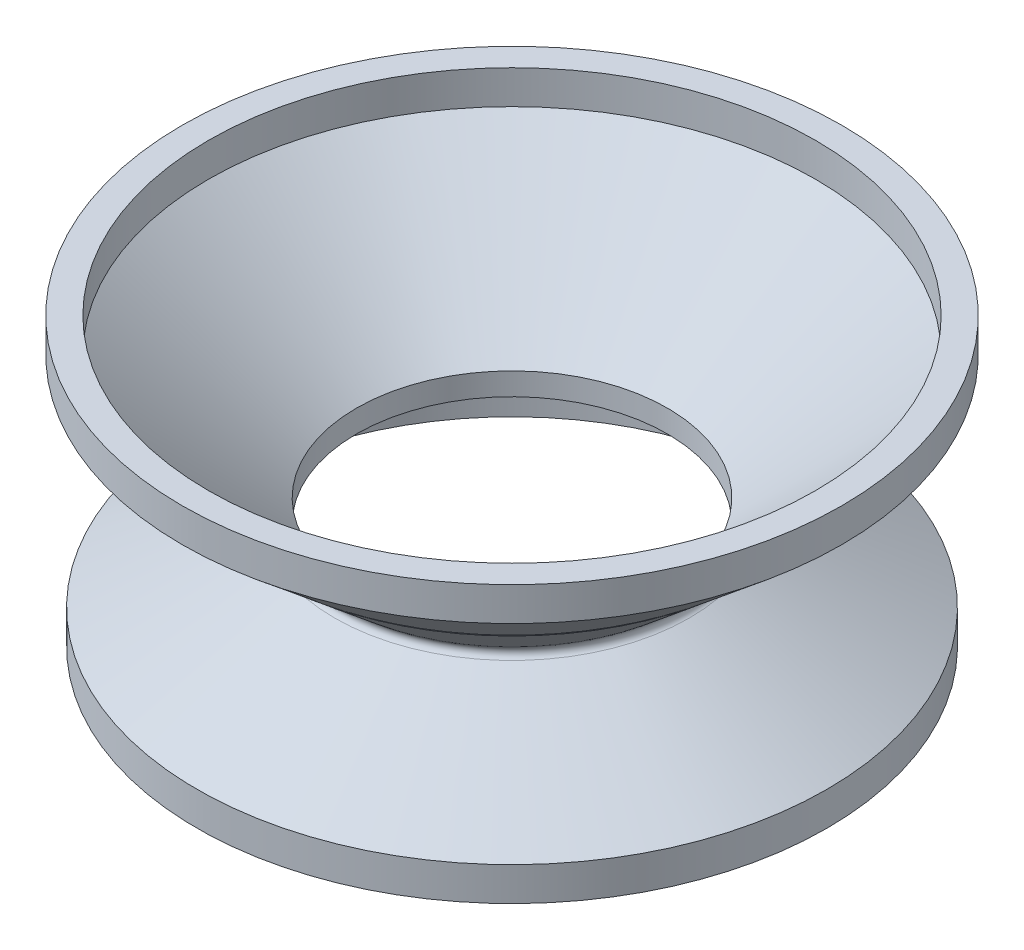
SolidWorks part; units mm, degrees
ref_plane "Front Plane" through (0, 0, 0) normal (0, 0, 1) x (1, 0, 0)
ref_plane "Top Plane" through (0, 0, 0) normal (0, 1, 0) x (1, 0, 0)
ref_plane "Right Plane" through (0, 0, 0) normal (1, 0, 0) x (0, 0, -1)
sketch "Sketch1" plane through (0, 0, 0) normal (0, 0, 1) x (1, 0, 0)
  line L0 (-42.6436, 0) -> (43.9692, 0) construction
  line L1 (0.6628, 0) -> (-4.0261, 3.9344)
  line L2 (0.6628, 0) -> (-7.9975, -5)
  line L3 (1.4628, -0.6928) -> (-5.9975, -5)
  line L5 (-8.8712, 8) -> (-7.3155, 8)
  line L6 (-7.9975, -5) -> (-5.9975, -5)
  line L7 (10.6845, 7.609) -> (10.6845, -7.609) construction
  line L8 (2.3996, -0.152) -> (-16.3835, 15.6089) construction
  line L9 (0.6628, 0) -> (-17.0263, 14.8429) construction
  line L10 (0.6628, 0) -> (-17.9865, -10.7671) construction
  line L11 (2.3996, -0.152) -> (-17.4865, -11.6332) construction
  line L12 (0.6628, 0) -> (2.2628, 0) construction
  line L13 (1.4628, -0.6928) -> (1.4628, 0.6341)
  line L14 (1.4628, 0.6341) -> (-7.3155, 8)
  line L15 (-4.3372, 4.1955) -> (-4.0261, 4.1955)
  line L16 (-4.0261, 4.1955) -> (-4.0261, 3.9344)
  line L17 (-4.3372, 4.1955) -> (-8.8712, 8)
  point P11 (1.4628, 0)
  point P21 (-3.5996, 4.1955)
  point P23 (0, 0)
  point P25 (-3.0114, 5.8297)
  dimension "D1" = 40
  dimension "D2" = 30
  dimension "D4" = 8
  dimension "D5" = 5
  dimension "D6" = 18
  dimension "D7" = 1.6
  dimension "D8" = 1
  dimension "D9" = 5
  dimension "D10" = 0.8
  dimension "D3" = 1
revolve "Revolve1" add sketch "Sketch1" angle 360 about L7
scale "Scale1" [suppressed]
fillet "Fillet2" radius 0.4 1 edges at (0.6628, 0, 0)
sketch "Sketch2" plane through (0, 8, 0) normal (0, 1, 0) x (1, 0, 0)
  circle A0 centre (10.6845, 0) radius 19.5557 construction
  circle A1 centre (10.6845, 0) radius 18 construction
  circle A2 centre (10.6845, 0) radius 19.5557
  circle A3 centre (10.6845, 0) radius 18
extrude "Boss-Extrude1" add sketch "Sketch2" along normal blind 2
sketch "Sketch3" plane through (0, -5, 0) normal (0, -1, 0) x (1, 0, 0)
  circle A0 centre (10.6845, 0) radius 16.6819 construction
  circle A1 centre (10.6845, 0) radius 18.6819 construction
  circle A2 centre (10.6845, 0) radius 16.6819
  circle A3 centre (10.6845, 0) radius 18.6819
extrude "Boss-Extrude2" add sketch "Sketch3" along normal blind 2
